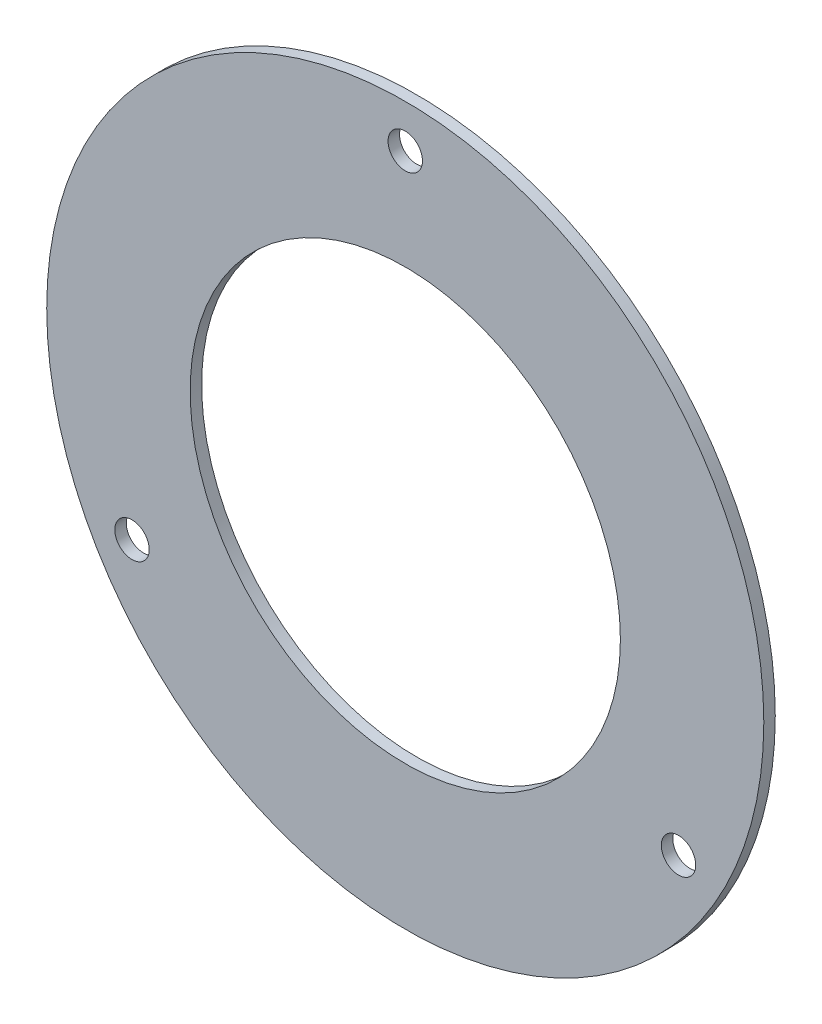
SolidWorks part; units mm, degrees
material "PTFE (general)"
ref_plane "Front Plane" through (0, 0, 0) normal (0, 0, 1) x (1, 0, 0)
ref_plane "Top Plane" through (0, 0, 0) normal (0, 1, 0) x (1, 0, 0)
ref_plane "Right Plane" through (0, 0, 0) normal (1, 0, 0) x (0, 0, -1)
sketch "Sketch1" plane through (0, 0, 0) normal (0, 0, 1) x (1, 0, 0)
  circle A0 centre (0, 0) radius 62.5
  circle A1 centre (0, 0) radius 37.5
  dimension "D1" = 125
  dimension "D2" = 75
extrude "Boss-Extrude1" add sketch "Sketch1" along normal blind 2
sketch "Sketch2" plane through (0, 0, 0) normal (0, 0, -1) x (-1, 0, 0)
  circle A0 centre (0, 55) radius 3
  dimension "D1" = 6
  dimension "D2" = 55
extrude "Cut-Extrude1" cut sketch "Sketch2" against normal through all
pattern_circular "CirPattern1" count 3 every 120 about axis through (0, 0, 0) along (0, 0, 1) of "Cut-Extrude1"
